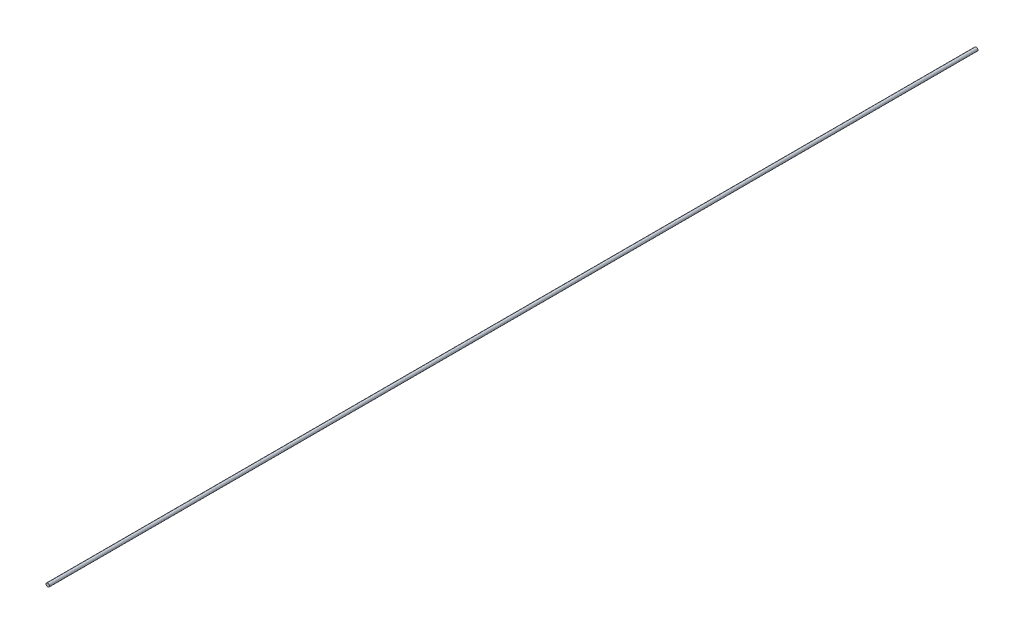
SolidWorks part; units mm, degrees
material "Hexcel AS4C (3000 丝)"
ref_plane "Front" through (0, 0, 0) normal (0, 0, 1) x (1, 0, 0)
ref_plane "Top" through (0, 0, 0) normal (0, 1, 0) x (1, 0, 0)
ref_plane "Right" through (0, 0, 0) normal (1, 0, 0) x (0, 0, -1)
other "Configuration Table"
sketch "草图1" plane through (0, 0, 0) normal (0, 0, 1) x (1, 0, 0)
  circle A0 centre (0, 0) radius 0.2
extrude "凸台-拉伸1" add sketch "草图1" along normal blind 108
